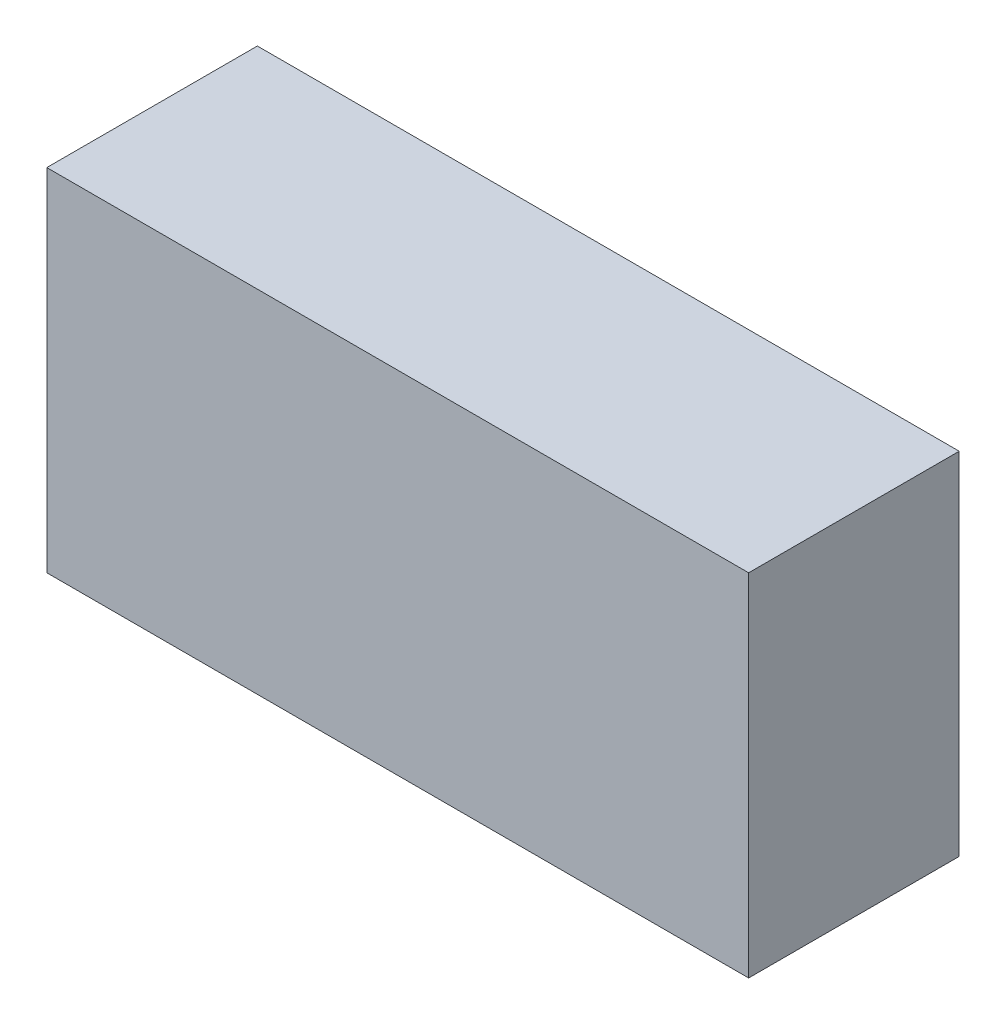
SolidWorks part; units mm, degrees
material "Лист 6,0 ГОСТ 19903-2015 / Ст3сп ГОСТ 14637-89"
ref_plane "Спереди" through (0, 0, 0) normal (0, 0, 1) x (1, 0, 0)
ref_plane "Сверху" through (0, 0, 0) normal (0, 1, 0) x (1, 0, 0)
ref_plane "Справа" through (0, 0, 0) normal (1, 0, 0) x (0, 0, -1)
sketch "Эскиз1" plane through (0, 0, 0) normal (0, 0, 1) x (1, 0, 0)
  line L1 (-10, -5) -> (10, -5)
  line L2 (-10, -5) -> (-10, 5)
  line L3 (-10, 5) -> (10, 5)
  line L4 (10, -5) -> (10, 5)
extrude "Бобышка-Вытянуть1" add sketch "Эскиз1" along normal blind 6
